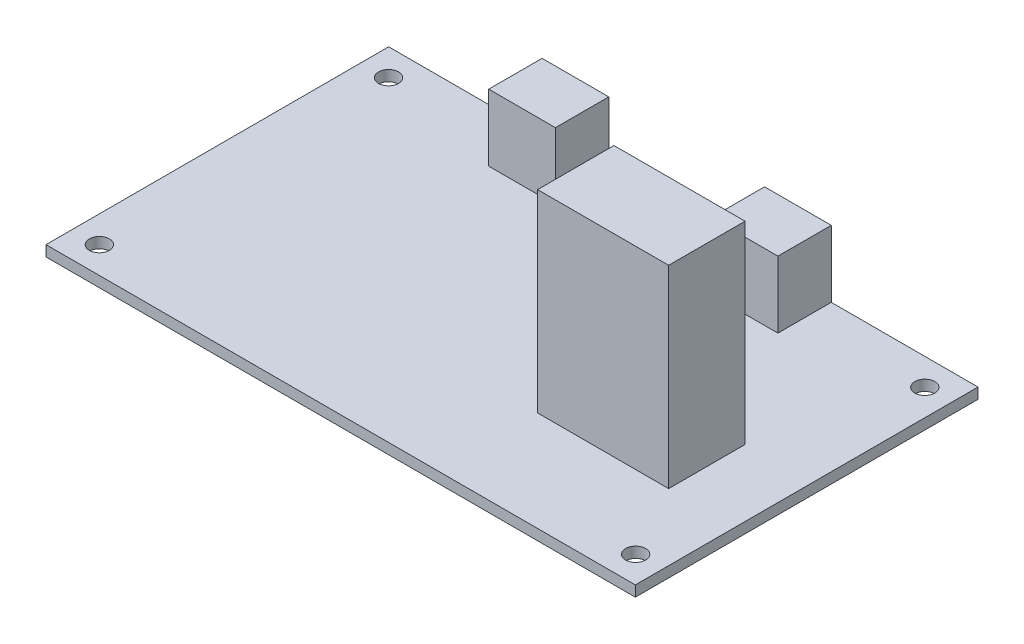
SolidWorks part; units mm, degrees
ref_plane "Plan de face" through (0, 0, 0) normal (0, 0, 1) x (1, 0, 0)
ref_plane "Plan de dessus" through (0, 0, 0) normal (0, 1, 0) x (1, 0, 0)
ref_plane "Plan de droite" through (0, 0, 0) normal (1, 0, 0) x (0, 0, -1)
sketch "Esquisse1" plane through (0, 0, 0) normal (0, 1, 0) x (1, 0, 0)
  line L1 (-31.2381, -19.8095) -> (57.1219, -19.8095)
  line L2 (-31.2381, -19.8095) -> (-31.2381, 31.5705)
  line L3 (-31.2381, 31.5705) -> (57.1219, 31.5705)
  line L4 (57.1219, -19.8095) -> (57.1219, 31.5705)
  circle A0 centre (-27.2381, -15.8095) radius 1.5
  circle A1 centre (53.1719, -15.8095) radius 1.5
  circle A2 centre (53.1719, 27.5505) radius 1.5
  circle A3 centre (-27.2381, 27.5505) radius 1.5
  dimension "D1" = 4
  dimension "D2" = 4
  dimension "D3" = 2
  dimension "D4" = 2
extrude "Boss.-Extru.2" add sketch "Esquisse1" along normal blind 1.6 contours L4 L3 L2 L1 | A1 | A2 | A3 | A0
sketch "Esquisse3" plane through (0, 1.6, 0) normal (0, 1, 0) x (1, 0, 0)
  line L0 (-31.2381, 31.5705) -> (57.1219, 31.5705) construction
  line L1 (35.1219, 31.5705) -> (25.1219, 31.5705)
  line L2 (35.1219, 31.5705) -> (35.1219, 23.5705)
  line L3 (35.1219, 23.5705) -> (25.1219, 23.5705)
  line L4 (25.1219, 31.5705) -> (25.1219, 23.5705)
  line L5 (57.1219, -19.8095) -> (57.1219, 31.5705) construction
  line L6 (-31.2381, -19.8095) -> (-31.2381, 31.5705) construction
  line L7 (1.7619, 31.5705) -> (-8.2381, 31.5705)
  line L8 (1.7619, 31.5705) -> (1.7619, 23.5705)
  line L9 (1.7619, 23.5705) -> (-8.2381, 23.5705)
  line L10 (-8.2381, 31.5705) -> (-8.2381, 23.5705)
  dimension "D1" = 22
  dimension "D2" = 23
extrude "Boss.-Extru.3" add sketch "Esquisse3" along normal blind 10
sketch "Esquisse4" plane through (0, 1.6, 0) normal (0, 1, 0) x (1, 0, 0)
  line L0 (57.1219, -19.8095) -> (57.1219, 31.5705) construction
  line L1 (47.1219, 6.6416) -> (27.4718, 6.6416)
  line L2 (47.1219, 6.6416) -> (47.1219, -4.8095)
  line L3 (47.1219, -4.8095) -> (27.4718, -4.8095)
  line L4 (27.4718, 6.6416) -> (27.4718, -4.8095)
  line L5 (-31.2381, -19.8095) -> (57.1219, -19.8095) construction
  dimension "D1" = 10
  dimension "D2" = 15
extrude "Boss.-Extru.4" add sketch "Esquisse4" along normal blind 29
